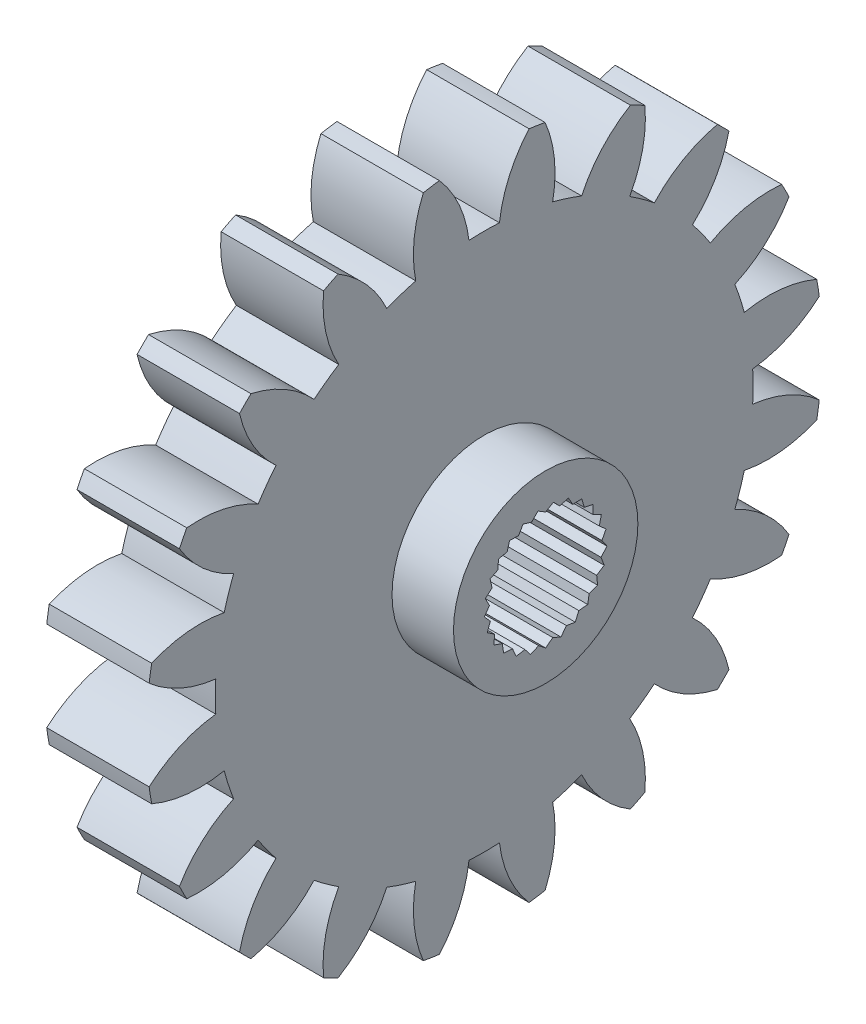
SolidWorks part; units mm, degrees
ref_plane "Plane1" through (0, 0, 0) normal (0, 0, 1) x (1, 0, 0)
ref_plane "Plane2" through (0, 0, 0) normal (0, 1, 0) x (1, 0, 0)
ref_plane "Plane3" through (0, 0, 0) normal (1, 0, 0) x (0, 0, -1)
other "Configuration Table"
sketch "HoldingSke" plane through (0, 0, 0) normal (0, 1, 0) x (1, 0, 0)
  line L0 (0, 0) -> (0.6265, -0.228)
  line L1 (-15, 0) -> (100, 0) construction
  line L2 (0, 0) -> (-2.1039, 2.3779)
  line L3 (0, 0) -> (-11.863, 4.5341)
  line L4 (0, 0) -> (8.1152, 2.9537)
  line L5 (0, 0) -> (-46.8476, -17.4728)
  line L6 (0, 0) -> (-4.1448, -2.7965)
  line L7 (-2.1039, 2.3779) -> (8.6586, 51.2059)
  line L8 (-76.2, 54.61) -> (-75.3, 54.61)
  line L9 (-71.009, 38.7566) -> (-53.1078, 45.2721)
  line L10 (-76.2, 71.12) -> (104.1128, 71.12)
  line L11 (0, 0) -> (-5, 0)
  line L12 (-76.2, 101.6) -> (-76.147, 101.6)
  line L13 (24.9733, 27.94) -> (52.9518, 28.4284)
  line L14 (24.9733, 27.94) -> (24.9743, 27.94)
  line L15 (24.9733, 27.94) -> (100.4006, 29.5858)
  line L16 (-63.627, -1.5) -> (-12.827, -1.5)
  circle A0 centre (0, 0) radius 2.5
  circle A1 centre (0, 0) radius 13.124
  circle A2 centre (0, 0) radius 37.5
  circle A3 centre (0, 0) radius 2.5
  dimension "MHD" = 26.248
  dimension "Hub_dia" = 75
  dimension "Bore" = 5
  dimension "MBD" = 5
  dimension "Num_teeth" = 20
  dimension "Pitch" = 0.6667
  dimension "Overall_len" = 50
  dimension "Show_teeth" = 20
  dimension "Thickness" = 5
  dimension "OAL" = 50.0001
  dimension "T_dim" = 0.9
  dimension "Ap" = 20
  dimension "H" = 19.05
  dimension "Pitch_radius" = 180.3128
  dimension "Width" = 5
  dimension "Backlash" = 0.053
  dimension "Addendum_fac" = 1
  dimension "Dedendum_fac" = 1.25
  dimension "Clearance_fac" = 0.25
  dimension "Dedendum_add" = 0.001
  dimension "Module" = 1.5
sketch "BasProSke" plane through (0, 0, 0) normal (0, 1, 0) x (1, 0, 0)
  line L0 (-10, 0) -> (60, 0) construction
  line L1 (0, 0) -> (0, 16.5)
  line L2 (0, 0) -> (5, 0)
  line L3 (5, 0) -> (5, 16.5)
  line L4 (5, 16.5) -> (0, 16.5)
  dimension "Thickness" = 5
  dimension "Diameter" = 33
revolve "Base-Revolve" add sketch "BasProSke" angle 360 about L0
sketch "TooCutSke" plane through (0, 0, 0) normal (1, 0, 0) x (0, 0, -1)
  line L1 (0, 0) -> (0, 107) construction
  line L2 (0, 0) -> (-1.2696, 14.9462) construction
  line L3 (0, 0) -> (-4.6808, 29.5532) construction
  line L4 (-1.2696, 14.9462) -> (-2.3404, 14.7766) construction
  arc A0 (0.7438, 13.1029) -> (-0.7438, 13.1029) centre (0, 0) ccw
  arc A1 (2.21, 16.377) -> (-2.21, 16.377) centre (0, 0) ccw
  circle A2 centre (0, 0) radius 15 construction
  circle A3 centre (0, 0) radius 14.0954 construction
  arc A4 (-0.7438, 13.1029) -> (-2.21, 16.377) centre (-6.7025, 12.3999) ccw
  arc A5 (2.21, 16.377) -> (0.7438, 13.1029) centre (6.7025, 12.3999) ccw
  dimension "Root_dia" = 26.248
  dimension "Overcut_dia" = 33.0508
  dimension "Pitch_dia" = 30
  dimension "Base_dia" = 28.1908
  dimension "Flank_rad" = 6
  dimension "Half_ang" = 9
  dimension "Half_CT" = 1.0841
extrude "ToothCut" cut sketch "TooCutSke" along normal through all
fillet "Breaks" [suppressed] radius 0.03
fillet "RootFillets" [suppressed] radius 0.376
pattern_circular "TeethCuts" count 20 every 18 about axis through (-10, 0, 0) along (1, 0, 0) of "ToothCut", "RootFillets", "Breaks"
sketch "HubNeaOneSke" plane through (0, 0, 0) normal (-1, 0, 0) x (0, 0, 1)
  circle A0 centre (0, 0) radius 13.124
  dimension "Diameter" = 26.248
extrude "HubNearOne" [suppressed] add sketch "HubNeaOneSke" along normal blind 45.0001
sketch "HubNeaBotSke" plane through (0, 0, 0) normal (-1, 0, 0) x (0, 0, 1)
  circle A0 centre (0, 0) radius 13.124
  dimension "Diameter" = 26.248
extrude "HubNearBoth" [suppressed] add sketch "HubNeaBotSke" along normal blind 22.5
ref_plane "FarPln" through (5, 0, 0) normal (1, 0, 0) x (0, 0, -1)
sketch "HubFarSke" plane through (5, 0, 0) normal (1, 0, 0) x (0, 0, -1)
  circle A0 centre (0, 0) radius 13.124
  dimension "Diameter" = 26.248
extrude "HubFar" [suppressed] add sketch "HubFarSke" along normal blind 22.5
sketch "BorSke" plane through (0, 0, 0) normal (1, 0, 0) x (0, 0, -1)
  circle A0 centre (0, 0) radius 2.5
  dimension "Diameter" = 5
extrude "Bore" cut sketch "BorSke" along normal mid plane 100.0001
sketch "KeySke" plane through (0, 0, 0) normal (1, 0, 0) x (0, 0, -1)
  line L0 (-1, 0) -> (-1, 3.4)
  line L1 (-1, 3.4) -> (1, 3.4)
  line L2 (1, 3.4) -> (1, 0)
  line L3 (0, 0) -> (0, 34) construction
  line L4 (-1, 0) -> (1, 0)
  dimension "Offset" = 3.4
  dimension "Width" = 2
extrude "Keyway" [suppressed] cut sketch "KeySke" along normal mid plane 100.0001
pattern_circular "Keyway2" [suppressed] count 2 every 90 about axis through (-10, 0, 0) along (1, 0, 0)
sketch "Sketch1" plane through (5, 0, 0) normal (1, 0, 0) x (0, 0, -1)
  circle A0 centre (0, 0) radius 4.5
  circle A1 centre (0, 0) radius 2.5
extrude "Boss-Extrude1" add sketch "Sketch1" along normal blind 3 contours A0 A1
sketch "Sketch2" plane through (8, 0, 0) normal (1, 0, 0) x (0, 0, -1)
  line L0 (0, 0) -> (-0.5197, -4.1142) construction
  line L1 (0, 0) -> (0, -3.7366) construction
  line L2 (0, 0) -> (0.4435, -3.5109) construction
  line L3 (-0.3447, -2.7283) -> (0, -3)
  line L4 (0, -3) -> (0.3447, -2.7283)
  circle A0 centre (0, 0) radius 2.75
  circle A1 centre (0, 0) radius 3 construction
  circle M8 centre (0, 0) radius 2.5
  dimension "D1" = 7.2
  dimension "D2" = 14.4
extrude "Cut-Extrude1" cut sketch "Sketch2" against normal through all contours A0 L3 L4 | A0 M8
pattern_circular "CirPattern1" count 25 over 360 about axis through (0, 0, 0) along (1, 0, 0) of "Cut-Extrude1"
equation "' \"Module@HoldingSke\" = 6.35"
equation "' \"Num_teeth@HoldingSke\" = 12"
equation "' \"Ap@HoldingSke\" =  20"
equation "' \"Ap@HoldingSke\" = 20"
equation "' \"Width@HoldingSke\" = 0.5 * 25.4"
equation "' \"Hub_dia@HoldingSke\"= 1 * 25.4"
equation "' \"Hub_dia@HoldingSke\" = 1 * 25.4"
equation "' \"Overall_len@HoldingSke\" = 1.0 * 25.4"
equation "' \"Bore@HoldingSke\" = 0.75 * 25.4"
equation "' \"T_dim@HoldingSke\" = 0.1 * 25.4"
equation "' \"Width@KeySke\" = 0.25 * 25.4"
equation "' \"Show_teeth@HoldingSke\" = 13"
equation "' \"Backlash@HoldingSke\" = 0.009 * 25.4"
equation "' \"Addendum_fac@HoldingSke\" = 1.0"
equation "' \"Dedendum_fac@HoldingSke\" = 1.25"
equation "' \"Dedendum_add@HoldingSke\" = 0.00005 * 25.4"
equation "' \"Clearance_fac@HoldingSke\" = 0.25"
equation "\"Pitch@HoldingSke\" = 1 / \"Module@HoldingSke\""
equation "\"Overcut_dia@TooCutSke\" = (\"Num_teeth@HoldingSke\" + 2 * \"Addendum_fac@HoldingSke\") / \"Pitch@HoldingSke\" + 0.002 * 25.4"
equation "\"Pitch_dia@TooCutSke\" = \"Num_teeth@HoldingSke\" / \"Pitch@HoldingSke\""
equation "\"Base_dia@TooCutSke\" = \"Num_teeth@HoldingSke\" / \"Pitch@HoldingSke\" * cos((\"Ap@HoldingSke\"  * 3.14159265 / 180))"
equation "\"Root_dia@TooCutSke\" = (\"Num_teeth@HoldingSke\" + 2) / \"Pitch@HoldingSke\" - 2 * (\"Addendum_fac@HoldingSke\" + \"Dedendum_fac@HoldingSke\") / \"Pitch@HoldingSke\" - \"Dedendum_add@HoldingSke\" * 2"
equation "\"Half_ang@TooCutSke\" = 180 / \"Num_teeth@HoldingSke\""
equation "\"Half_CT@TooCutSke\" = \"Num_teeth@HoldingSke\" / \"Pitch@HoldingSke\" * sin((3.14159265 / 2 / \"Num_teeth@HoldingSke\")) / 2 - 7 * \"Backlash@HoldingSke\" / 4"
equation "\"Flank_rad@TooCutSke\" = \"Num_teeth@HoldingSke\" / \"Pitch@HoldingSke\" / 5"
equation "\"Radius@RootFillets\" = \"Clearance_fac@HoldingSke\" / \"Pitch@HoldingSke\" + \"Dedendum_add@HoldingSke\""
equation "\"Break_rad@Breaks\" = 0.02 / \"Pitch@HoldingSke\""
equation "\"Thickness@HoldingSke\" = \"Width@HoldingSke\""
equation "\"OAL@HoldingSke\" = \"Thickness@HoldingSke\""
equation "\"MHD@HoldingSke\" = (\"Num_teeth@HoldingSke\" + 2) / \"Pitch@HoldingSke\" - 2 * (\"Addendum_fac@HoldingSke\" + \"Dedendum_fac@HoldingSke\")  / \"Pitch@HoldingSke\" - \"Dedendum_add@HoldingSke\" * 2"
equation "\"MBD@HoldingSke\" = (\"Num_teeth@HoldingSke\" + 2) / \"Pitch@HoldingSke\" - 2 * (\"Addendum_fac@HoldingSke\" + \"Dedendum_fac@HoldingSke\")  / \"Pitch@HoldingSke\" - \"Dedendum_add@HoldingSke\" * 2 - 0.002 * 25.4"
equation "\"MHD@HoldingSke\" = ((sgn( \"MHD@HoldingSke\" - \"Hub_dia@HoldingSke\" )-1)*( \"MHD@HoldingSke\" - \"Hub_dia@HoldingSke\" ))/-2+ \"Hub_dia@HoldingSke\""
equation "\"MBD@HoldingSke\" = ((sgn( \"MBD@HoldingSke\" - \"Bore@HoldingSke\" )-1)*( \"MBD@HoldingSke\" - \"Bore@HoldingSke\" ))/-2+ \"Bore@HoldingSke\""
equation "\"OAL@HoldingSke\" = ((sgn( \"OAL@HoldingSke\" - \"Overall_len@HoldingSke\" )+1)*( \"OAL@HoldingSke\" - \"Overall_len@HoldingSke\" ))/2 + \"Overall_len@HoldingSke\" + 0.000002 * 25.4"
equation "\"Num_teeth@TeethCuts\" = int( \"Show_teeth@HoldingSke\" ) + 1"
equation "\"Num_teeth@TeethCuts\" = ((sgn( \"Num_teeth@TeethCuts\" - \"Num_teeth@HoldingSke\" )-1)*( \"Num_teeth@TeethCuts\" - \"Num_teeth@HoldingSke\" ))/-2+ \"Num_teeth@HoldingSke\""
equation "\"Num_teeth@TeethCuts\" = ((sgn( \"Num_teeth@TeethCuts\" - 2.0)+1)*( \"Num_teeth@TeethCuts\" - 2.0))/2 +2.0"
equation "\"Angle@TeethCuts\" = 360.0 / \"Num_teeth@HoldingSke\""
equation "\"Diameter@BasProSke\" = (\"Num_teeth@HoldingSke\" + 2 * \"Addendum_fac@HoldingSke\") / \"Pitch@HoldingSke\""
equation "\"Thickness@BasProSke\"  = \"Thickness@HoldingSke\""
equation "' \"Fillet_rad@BasProSke\" =  \"Thickness@HoldingSke\" * 0.05"
equation "' \"Fillet_rad@BasProSke\" = \"Thickness@HoldingSke\" * 0.05"
equation "\"MHD@HoldingSke\" = ((sgn( \"MHD@HoldingSke\" - \"Root_dia@TooCutSke\" )-1)*( \"MHD@HoldingSke\" - \"Root_dia@TooCutSke\" ))/-2+ \"Root_dia@TooCutSke\""
equation "\"Diameter@HubNeaOneSke\" = \"MHD@HoldingSke\""
equation "\"Length@HubNearOne\" = \"OAL@HoldingSke\" - \"Thickness@BasProSke\""
equation "\"Diameter@HubNeaBotSke\" = \"MHD@HoldingSke\""
equation "\"Length@HubNearBoth\" = ( \"OAL@HoldingSke\" - \"Thickness@BasProSke\" ) / 2.0"
equation "\"Thickness@FarPln\" = \"Thickness@BasProSke\""
equation "\"Diameter@HubFarSke\" = \"MHD@HoldingSke\""
equation "\"Length@HubFar\" = ( \"OAL@HoldingSke\" - \"Thickness@BasProSke\" ) / 2.0"
equation "\"Diameter@BorSke\" = \"MBD@HoldingSke\""
equation "\"D1@Bore\" = \"OAL@HoldingSke\" * 2.0"
equation "\"D1@Keyway\" = \"OAL@HoldingSke\" * 2.0"
equation "\"Offset@KeySke\" = \"T_dim@HoldingSke\" + \"MBD@HoldingSke\" / 2.0"
